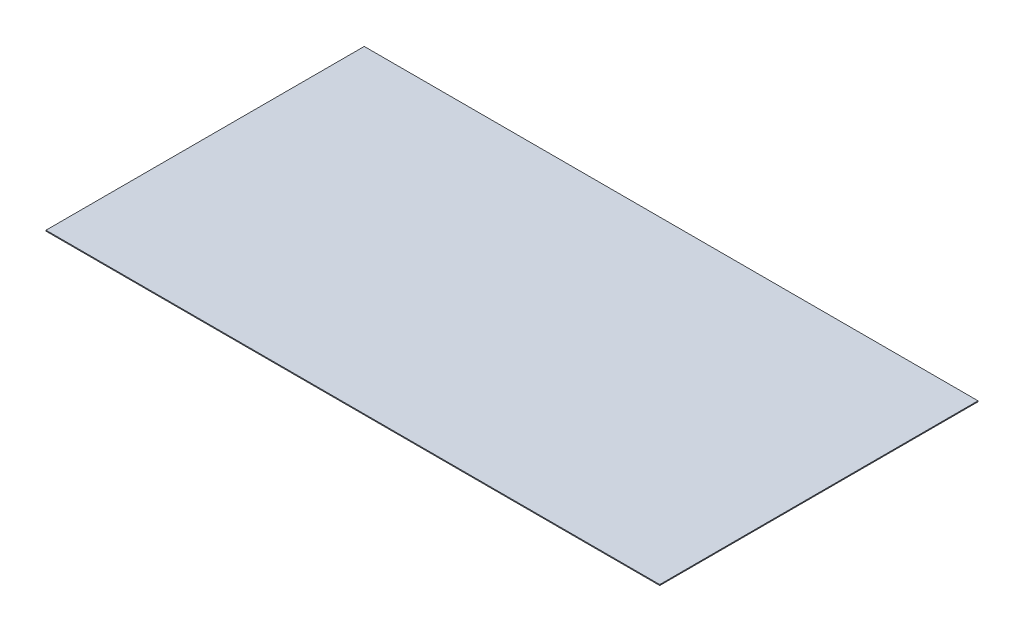
SolidWorks part; units mm, degrees
ref_plane "Спереди" through (0, 0, 0) normal (0, 0, 1) x (1, 0, 0)
ref_plane "Сверху" through (0, 0, 0) normal (0, 1, 0) x (1, 0, 0)
ref_plane "Справа" through (0, 0, 0) normal (1, 0, 0) x (0, 0, -1)
sketch "MASTER_FOOTPRINT" plane through (0, 0, 0) normal (0, 1, 0) x (1, 0, 0)
  line L1 (0, 0) -> (1350, 0)
  line L2 (0, 0) -> (0, 700)
  line L3 (0, 700) -> (1350, 700)
  line L4 (1350, 0) -> (1350, 700)
  dimension "D1" = 1350
  dimension "D2" = 700
extrude "BATH_BASE_PLATE" add sketch "MASTER_FOOTPRINT" along normal blind 2
equation "\"AI_Q_Peak\"= 0.006"
equation "\"AI_B_Bath\"= 700"
equation "\"AI_L_Settle\"= 900"
equation "\"AI_L_Inlet\"= 250"
equation "\"AI_L_Outlet\"= 200"
equation "\"AI_L_Bath\"= 1350"
equation "\"AI_H_Water\"= 550"
equation "\"AI_H_Freeboard\"= 200"
equation "\"AI_H_Bath\"= 750"
equation "\"AI_Shell_Thickness\"= 2"
equation "\"AI_Inlet_DN\"= 100"
equation "\"AI_Weir_Width\"= 600"
equation "\"AI_Inlet_Baffle_Offset\"= 125"
equation "\"AI_Distributor_Open_Area\"= 0.28"
equation "\"AI_Distributor_Hole_Dia\"= 22"
equation "\"AI_Distributor_Blind_Zone\"= 110"
equation "\"AI_Outlet_Baffle_Depth\"= 250"
equation "\"AI_Screw_Diameter\"= 100"
equation "\"AI_Screw_Pitch\"= 100"
equation "\"AI_Screw_Angle\"= 30"
equation "\"AI_Screw_Rpm\"= 15"
equation "\"AI_Screw_Clearance\"= 5"
equation "\"AI_Liner_Thickness\"= 5"
equation "\"AI_Discharge_Height\"= 650"
equation "\"AI_Frame_Height\"= 500"
